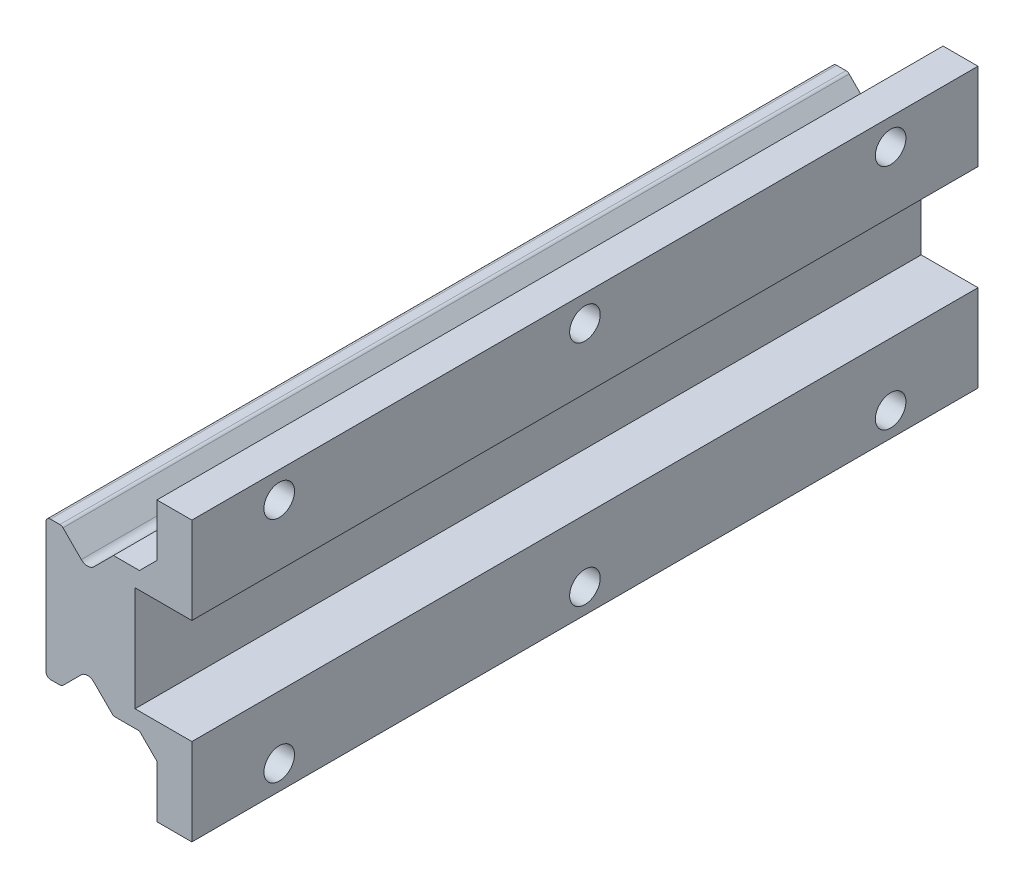
SolidWorks part; units mm, degrees
ref_plane "Front Plane" through (0, 0, 0) normal (0, 0, 1) x (1, 0, 0)
ref_plane "Top Plane" through (0, 0, 0) normal (0, 1, 0) x (1, 0, 0)
ref_plane "Right Plane" through (0, 0, 0) normal (1, 0, 0) x (0, 0, -1)
sketch "Sketch1" plane through (0, 0, 0) normal (0, 0, 1) x (1, 0, 0)
  line L0 (0.0622, 0) -> (0.0622, -0.0793) construction
  line L1 (-0.23, -0.2933) -> (-0.1874, -0.2933) construction
  line L2 (-0.23, -0.2933) -> (-0.23, 0) construction
  line L3 (-0.23, 0.2933) -> (-0.1874, 0.2933)
  line L4 (0.23, 0) -> (0.23, 0.2933) construction
  line L5 (-0.23, -0.2933) -> (-0.0201, -0.0256) construction
  line L6 (-0.23, 0.2933) -> (-0.0201, 0.0256) construction
  line L7 (-0.1874, 0.2933) -> (-0.1874, 0.2389) construction
  line L8 (-0.23, 0) -> (0.23, 0) construction
  line L9 (-0.1049, 0.2933) -> (-0.1049, 0.2108)
  line L10 (-0.0201, 0.2933) -> (-0.0201, 0.2108)
  line L11 (-0.1049, 0.2108) -> (-0.0201, 0.2108) construction
  line L12 (-0.1874, 0.2933) -> (-0.1049, 0.2108)
  line L13 (-0.1049, 0.2108) -> (-0.0624, 0.1683)
  line L14 (0.0622, 0.2933) -> (-0.0201, 0.2108)
  line L15 (-0.0201, 0.2108) -> (-0.0624, 0.1683)
  line L16 (-0.0624, 0.1683) -> (-0.1014, 0.1293) construction
  line L17 (-0.1014, 0.1293) -> (-0.1049, 0.1257) construction
  line L18 (-0.0624, 0.1683) -> (-0.0201, 0.1259) construction
  line L19 (-0.1049, 0.2108) -> (-0.1049, 0.1338) construction
  line L20 (-0.1049, 0.1257) -> (-0.1049, 0) construction
  line L21 (-0.1049, 0.1338) -> (-0.1049, 0.1257) construction
  line L22 (-0.0201, 0.2108) -> (-0.0201, 0.1259) construction
  line L23 (-0.0201, 0) -> (-0.0201, -0.0256) construction
  line L24 (-0.1049, 0) -> (-0.1049, -0.1338) construction
  line L25 (-0.1049, -0.1338) -> (-0.1049, -0.2933) construction
  line L26 (-0.0201, -0.0256) -> (-0.0201, -0.2933) construction
  line L27 (0.0622, -0.0793) -> (0.0622, -0.2933) construction
  line L28 (-0.1874, 0.2933) -> (-0.1049, 0.2933) construction
  line L29 (0.0622, 0.2933) -> (0.23, 0.2933) construction
  line L30 (-0.1049, 0.2933) -> (-0.0201, 0.2933) construction
  line L31 (-0.0201, 0.2933) -> (0.0622, 0.2933) construction
  line L32 (-0.1874, 0.2389) -> (-0.1874, 0) construction
  line L33 (-0.1874, -0.2389) -> (-0.1874, -0.2933) construction
  line L34 (-0.1874, 0) -> (-0.1874, -0.2389) construction
  line L35 (-0.0201, 0.1259) -> (-0.0201, 0.0256) construction
  line L36 (0.0622, 0.2933) -> (0.0622, 0.0793) construction
  line L37 (0.0622, 0.0793) -> (0.0622, 0) construction
  line L38 (-0.0201, 0.0256) -> (-0.0201, 0) construction
  line L39 (-0.0201, 0.0256) -> (0, 0) construction
  line L40 (0, 0) -> (0.23, -0.2933) construction
  line L41 (-0.0201, -0.0256) -> (0, 0) construction
  line L42 (0, 0) -> (0.23, 0.2933) construction
  line L43 (-0.1049, -0.2108) -> (-0.0624, -0.1683) construction
  line L44 (-0.1874, -0.2933) -> (-0.1049, -0.2108) construction
  line L45 (0.0622, -0.2933) -> (-0.0201, -0.2108) construction
  line L46 (-0.0201, -0.2108) -> (-0.0624, -0.1683) construction
  line L47 (-0.1874, -0.2933) -> (-0.1049, -0.2933) construction
  line L48 (0.0622, -0.2933) -> (0.23, -0.2933) construction
  line L49 (-0.1049, -0.2933) -> (-0.0201, -0.2933) construction
  line L50 (-0.0201, -0.2933) -> (0.0622, -0.2933) construction
  line L51 (-0.23, 0.3132) -> (-0.1874, 0.3132)
  line L52 (-0.1732, 0.3074) -> (-0.0908, 0.2249)
  line L53 (-0.0908, 0.2249) -> (-0.0766, 0.2108) construction
  line L54 (-0.0342, 0.2249) -> (-0.0483, 0.2108) construction
  line L55 (0.0539, 0.3133) -> (-0.0342, 0.225)
  line L56 (0.0539, 0.3133) -> (0.25, 0.3133)
  line L57 (0.25, -0.3132) -> (0.25, 0.3133)
  line L58 (0.0539, -0.3132) -> (0.25, -0.3132)
  line L59 (0.0539, -0.3132) -> (-0.0342, -0.225)
  line L60 (-0.0342, -0.2249) -> (-0.0625, -0.1966) construction
  line L61 (-0.0908, -0.2249) -> (-0.0625, -0.1966) construction
  line L62 (-0.1732, -0.3074) -> (-0.0908, -0.2249)
  line L63 (-0.23, -0.3132) -> (-0.1874, -0.3132)
  line L64 (-0.25, -0.2932) -> (-0.25, 0.2932)
  line L65 (-0.1791, -0.3132) -> (-0.0908, -0.2249) construction
  line L66 (-0.25, -0.3132) -> (-0.1791, -0.3132) construction
  line L67 (-0.1791, 0.3132) -> (-0.0908, 0.2249) construction
  line L68 (-0.25, 0.3132) -> (-0.1791, 0.3132) construction
  line L69 (-0.25, -0.3132) -> (-0.25, 0.3132) construction
  line L70 (0.0539, 0.3133) -> (-0.0342, 0.2249) construction
  line L71 (0.0539, -0.3132) -> (-0.0342, -0.2249) construction
  line L72 (-0.0766, 0.2108) -> (-0.0625, 0.1966) construction
  line L73 (-0.0908, 0.2249) -> (-0.0625, 0.1966) construction
  line L74 (-0.0483, 0.2108) -> (-0.0625, 0.1966) construction
  line L75 (-0.0342, 0.2249) -> (-0.0625, 0.1966) construction
  line L76 (-0.23, 0) -> (-0.23, 0.2933) construction
  line L77 (-0.23, -0.2933) -> (-0.23, 0.2933) construction
  line L78 (0.23, -0.2933) -> (0.23, 0) construction
  line L79 (0.23, -0.2933) -> (0.23, 0.2933) construction
  arc A0 (-0.1732, -0.3074) -> (-0.1874, -0.3132) centre (-0.1874, -0.2933) cw
  arc A1 (-0.1732, 0.3074) -> (-0.1874, 0.3132) centre (-0.1874, 0.2933) ccw
  arc A2 (-0.25, 0.2932) -> (-0.23, 0.3132) centre (-0.23, 0.2933) cw
  arc A3 (-0.23, -0.3132) -> (-0.25, -0.2932) centre (-0.23, -0.2933) cw
  arc A4 (-0.0342, 0.225) -> (-0.0908, 0.2249) centre (-0.0625, 0.2532) cw
  arc A5 (-0.0342, -0.225) -> (-0.0908, -0.2249) centre (-0.0625, -0.2532) ccw
  point P0 (0, 0)
  point P16 (-0.0201, 0)
  point P17 (-0.1049, 0)
  point P18 (-0.0201, 0)
  point P19 (-0.1049, 0.2108)
  dimension "D8" = 0.02
  dimension "D9" = 0.02
  dimension "D10" = 0.04
  dimension "D11" = 0.04
  dimension "D1" = 0.46
  dimension "D2" = 0.5865
  dimension "D3" = 0.1678
  dimension "D4" = 0.0426
  dimension "D5" = 0.1251
  dimension "D6" = 0.2501
  dimension "D7" = 0.2108
sketch "Sketch2" plane through (0, 0, 0) normal (0, 0, 1) x (1, 0, 0)
  line L0 (-0.23, -0.3132) -> (-0.1874, -0.3132) construction
  line L1 (-0.1732, -0.3074) -> (-0.0908, -0.2249) construction
  line L2 (0.0539, -0.3132) -> (-0.0342, -0.225) construction
  line L3 (0.0539, -0.3132) -> (0.25, -0.3132) construction
  line L4 (0.25, -0.3132) -> (0.25, 0.3133) construction
  line L5 (0.0539, 0.3133) -> (0.25, 0.3133) construction
  line L6 (0.0539, 0.3133) -> (-0.0342, 0.225) construction
  line L7 (-0.0201, 0.2933) -> (-0.0201, 0.2108) construction
  line L8 (-0.1732, 0.3074) -> (-0.0908, 0.2249) construction
  line L9 (-0.23, 0.3132) -> (-0.1874, 0.3132) construction
  line L10 (-0.25, -0.2933) -> (-0.25, 0.2932) construction
  line L11 (-0.23, -0.3132) -> (-0.1874, -0.3132)
  line L12 (-0.1732, -0.3074) -> (-0.0908, -0.2249)
  line L13 (0.0539, -0.3132) -> (-0.0342, -0.225)
  line L14 (0.0539, -0.3132) -> (0.25, -0.3132)
  line L15 (0.25, -0.3132) -> (0.25, 0.3133)
  line L16 (0.0539, 0.3133) -> (0.25, 0.3133)
  line L17 (0.0539, 0.3133) -> (-0.0342, 0.225)
  line L18 (-0.0201, 0.2933) -> (-0.0201, 0.2108)
  line L19 (-0.1732, 0.3074) -> (-0.0908, 0.2249)
  line L20 (-0.23, 0.3132) -> (-0.1874, 0.3132)
  line L21 (-0.25, -0.2933) -> (-0.25, 0.2932)
  line L22 (36.1101, 5.2347) -> (33.8705, 7.4743)
  line L23 (41.0915, 5.2347) -> (41.0915, 21.1478)
  line L25 (30.341, 21.0018) -> (32.4356, 18.9073)
  line L26 (28.3915, 5.7455) -> (28.3915, 20.6426)
  line L27 (30.341, 5.3863) -> (32.4356, 7.4809)
  line L28 (36.113, 21.1478) -> (33.8734, 18.9082)
  line L29 (28.8995, 5.2375) -> (29.9818, 5.2375)
  line L30 (28.8995, 21.1506) -> (29.9818, 21.1506)
  line L31 (36.1101, 5.2347) -> (41.0915, 5.2347)
  line L32 (36.113, 21.1478) -> (41.0915, 21.1478)
  arc A0 (-0.25, -0.2933) -> (-0.23, -0.3132) centre (-0.23, -0.2933) ccw construction
  arc A1 (-0.1874, -0.3132) -> (-0.1732, -0.3074) centre (-0.1874, -0.2933) ccw construction
  arc A2 (-0.0342, -0.225) -> (-0.0908, -0.2249) centre (-0.0625, -0.2532) ccw construction
  arc A3 (-0.0908, 0.2249) -> (-0.0342, 0.225) centre (-0.0625, 0.2532) ccw construction
  arc A4 (-0.1732, 0.3074) -> (-0.1874, 0.3132) centre (-0.1874, 0.2933) ccw construction
  arc A5 (-0.23, 0.3132) -> (-0.25, 0.2932) centre (-0.23, 0.2933) ccw construction
  arc A6 (-0.25, -0.2933) -> (-0.23, -0.3132) centre (-0.23, -0.2933) ccw
  arc A7 (-0.1874, -0.3132) -> (-0.1732, -0.3074) centre (-0.1874, -0.2933) ccw
  arc A8 (-0.0342, -0.225) -> (-0.0908, -0.2249) centre (-0.0625, -0.2532) ccw
  arc A9 (-0.0908, 0.2249) -> (-0.0342, 0.225) centre (-0.0625, 0.2532) ccw
  arc A10 (-0.1732, 0.3074) -> (-0.1874, 0.3132) centre (-0.1874, 0.2933) ccw
  arc A11 (-0.23, 0.3132) -> (-0.25, 0.2932) centre (-0.23, 0.2933) ccw
  arc A12 (28.8995, 21.1506) -> (28.3915, 20.6426) centre (28.8995, 20.6426) ccw
  arc A13 (29.9818, 5.2375) -> (30.341, 5.3863) centre (29.9818, 5.7455) ccw
  arc A14 (30.341, 21.0018) -> (29.9818, 21.1506) centre (29.9818, 20.6426) ccw
  arc A15 (32.4356, 18.9073) -> (33.8734, 18.9082) centre (33.154, 19.6257) ccw
  arc A16 (33.8705, 7.4743) -> (32.4356, 7.4809) centre (33.1497, 6.7582) ccw
  arc A17 (28.3915, 5.7455) -> (28.8995, 5.2375) centre (28.8995, 5.7455) ccw
  dimension "D2" = 0.508
  dimension "D3" = 1.016
  dimension "D9" = 1.016
  dimension "D1" = 15.9131
  dimension "D4" = 14.8971
  dimension "D5" = 12.7
  dimension "D6" = 45
  dimension "D7" = 90
  dimension "D8" = 90
  dimension "D10" = 1.0823
  dimension "D11" = 1.0823
  dimension "D12" = 4.9814
  dimension "D13" = 4.9786
  dimension "D14" = 3.1673
  dimension "D15" = 3.1673
  dimension "D16" = 2.9622
  dimension "D17" = 2.9622
sketch "Sketch3" plane through (0, 0, 0) normal (0, 0, 1) x (1, 0, 0)
  line L0 (28.8995, 5.2375) -> (29.9818, 5.2375) construction
  line L1 (30.341, 5.3863) -> (32.4356, 7.4809) construction
  line L2 (36.1101, 5.2347) -> (33.8705, 7.4743) construction
  line L3 (36.1101, 5.2347) -> (41.0915, 5.2347) construction
  line L4 (41.0915, 5.2347) -> (41.0915, 21.1478) construction
  line L5 (36.113, 21.1478) -> (41.0915, 21.1478) construction
  line L6 (36.113, 21.1478) -> (33.8734, 18.9082) construction
  line L7 (30.341, 21.0018) -> (32.4356, 18.9073) construction
  line L8 (28.8995, 21.1506) -> (29.9818, 21.1506) construction
  line L9 (28.3915, 5.7455) -> (28.3915, 20.6426) construction
  line L10 (28.8995, 5.2375) -> (29.9818, 5.2375)
  line L11 (30.341, 5.3863) -> (32.4356, 7.4809)
  line L12 (36.1101, 5.2347) -> (33.8705, 7.4743)
  line L13 (36.1101, 5.2347) -> (39.0915, 5.2347)
  line L14 (41.0915, 5.2347) -> (41.0915, 13.1912) construction
  line L15 (36.113, 21.1478) -> (39.0915, 21.1478)
  line L16 (36.113, 21.1478) -> (33.8734, 18.9082)
  line L17 (30.341, 21.0018) -> (32.4356, 18.9073)
  line L18 (28.8995, 21.1506) -> (29.9818, 21.1506)
  line L19 (28.3915, 5.7455) -> (28.3915, 20.6426)
  line L20 (28.3915, 13.1941) -> (41.0915, 13.1912) construction
  line L21 (41.0915, 23.1478) -> (41.0915, 29.1478)
  line L22 (41.0897, 3.2347) -> (41.0844, -2.7653)
  line L23 (39.0915, 21.1478) -> (41.0915, 23.1478)
  line L24 (39.0915, 5.2347) -> (41.0897, 3.2347)
  line L25 (38.5915, 19.1912) -> (45.0915, 19.1912)
  line L27 (38.5915, 19.1912) -> (38.5915, 7.1912)
  line L28 (41.088, 5.2347) -> (41.0915, 5.2347)
  line L29 (38.5915, 7.1912) -> (45.0915, 7.1912)
  line L34 (41.0915, 13.1912) -> (41.0915, 19.1912) construction
  line L35 (41.0915, 19.1912) -> (41.0915, 21.1478) construction
  line L36 (41.0888, 7.1912) -> (41.0915, 5.2347) construction
  line L37 (41.0915, 29.1478) -> (45.0915, 29.1478)
  line L38 (41.0844, -2.7653) -> (45.0915, -2.7653)
  line L39 (45.0915, 29.1478) -> (45.0915, -2.7653)
  arc A0 (28.3915, 5.7455) -> (28.8995, 5.2375) centre (28.8995, 5.7455) ccw construction
  arc A1 (29.9818, 5.2375) -> (30.341, 5.3863) centre (29.9818, 5.7455) ccw construction
  arc A2 (33.8705, 7.4743) -> (32.4356, 7.4809) centre (33.1497, 6.7582) ccw construction
  arc A3 (32.4356, 18.9073) -> (33.8734, 18.9082) centre (33.154, 19.6257) ccw construction
  arc A4 (30.341, 21.0018) -> (29.9818, 21.1506) centre (29.9818, 20.6426) ccw construction
  arc A5 (28.8995, 21.1506) -> (28.3915, 20.6426) centre (28.8995, 20.6426) ccw construction
  arc A6 (28.3915, 5.7455) -> (28.8995, 5.2375) centre (28.8995, 5.7455) ccw
  arc A7 (29.9818, 5.2375) -> (30.341, 5.3863) centre (29.9818, 5.7455) ccw
  arc A8 (33.8705, 7.4743) -> (32.4356, 7.4809) centre (33.1497, 6.7582) ccw
  arc A9 (32.4356, 18.9073) -> (33.8734, 18.9082) centre (33.154, 19.6257) ccw
  arc A10 (30.341, 21.0018) -> (29.9818, 21.1506) centre (29.9818, 20.6426) ccw
  arc A11 (28.8995, 21.1506) -> (28.3915, 20.6426) centre (28.8995, 20.6426) ccw
  dimension "D1" = 8
  dimension "D2" = 12
  dimension "D3" = 4
  dimension "D4" = 6.5
  dimension "D5" = 9.9565
  dimension "D6" = 9.9566
extrude "Boss-Extrude1" add sketch "Sketch3" along normal blind 90
sketch "Эскиз1" plane through (41.0915, 0, 0) normal (-1, 0, 0) x (0, 0, 1)
  line L0 (0, 26.1478) -> (90, 26.1478) construction
  line L1 (0, 23.1478) -> (0, 29.1478) construction
  line L2 (90, 23.1478) -> (90, 29.1478) construction
  line L3 (0, 0) -> (90, 0.2347) construction
  line L4 (90, 3.2347) -> (90, -2.7653) construction
  line L5 (0, 3.2347) -> (0, -2.7653) construction
  circle A0 centre (10, 0.0261) radius 1.75
  circle A1 centre (45, 0.0261) radius 1.75
  circle A2 centre (80, 0.0261) radius 1.75
  circle A3 centre (45, 26.1478) radius 1.75
  circle A4 centre (80, 26.1478) radius 1.75
  circle A5 centre (10, 26.1478) radius 1.75
  point P13 (0, 0)
  point P14 (46.469, 26.9614)
  point P15 (45, 26.1478)
  dimension "D1" = 3.5
  dimension "D4" = 35
  dimension "D5" = 10
  dimension "D2" = 3
  dimension "D3" = 2
extrude "Вырез-Вытянуть3" cut sketch "Эскиз1" against normal through all both and the other way through all
